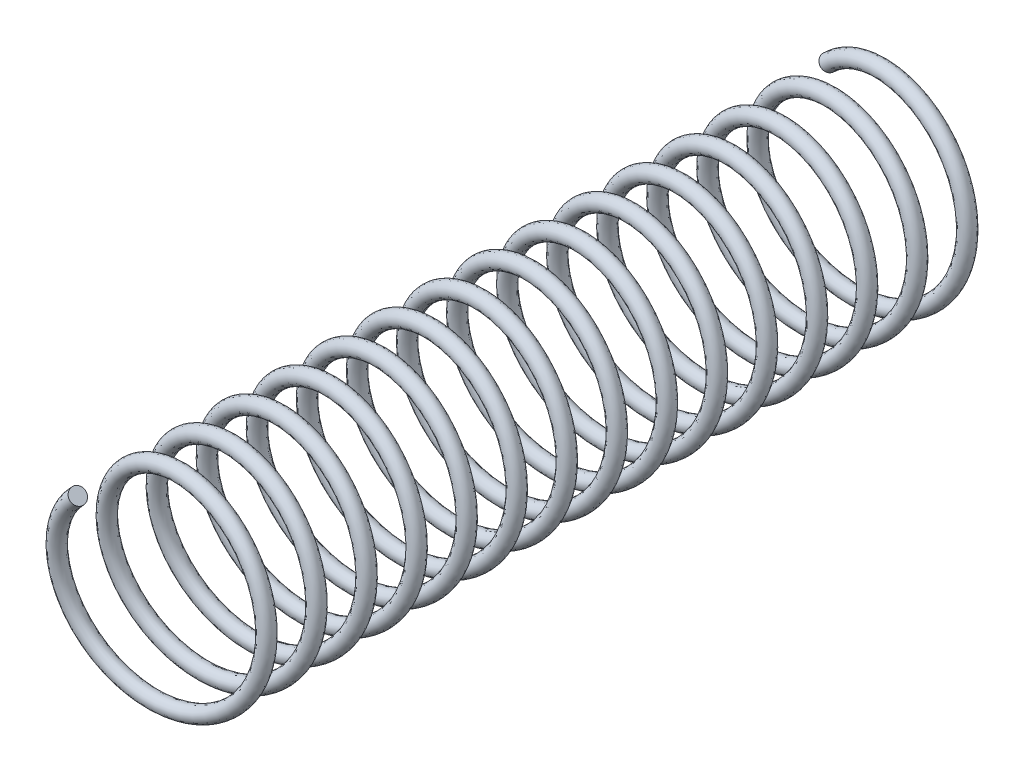
SolidWorks part; units mm, degrees
ref_plane "Front Plane" through (0, 0, 0) normal (0, 0, 1) x (1, 0, 0)
ref_plane "Top Plane" through (0, 0, 0) normal (0, 1, 0) x (1, 0, 0)
ref_plane "Right Plane" through (0, 0, 0) normal (1, 0, 0) x (0, 0, -1)
sketch "Sketch1" plane through (0, 0, 0) normal (0, 0, 1) x (1, 0, 0)
  circle A0 centre (0, 0) radius 7.62
  dimension "D1" = 15.24
curve "Helix/Spiral1" pitch 4.1487 height 62.23 turns 15
ref_plane "Plane1" through (-5.3882, 5.3882, 62.23) normal (0.7045, 0.7045, 0.0863) x (0.061, 0.061, -0.9963)
sketch "Sketch2" plane through (-5.3882, 5.3882, 62.23) normal (0.7045, 0.7045, 0.0863) x (0.061, 0.061, -0.9963)
  circle A0 centre (0, 0) radius 0.635
  dimension "D1" = 1.27
sweep "Sweep1" add profiles "Sketch2" path "Helix/Spiral1"
